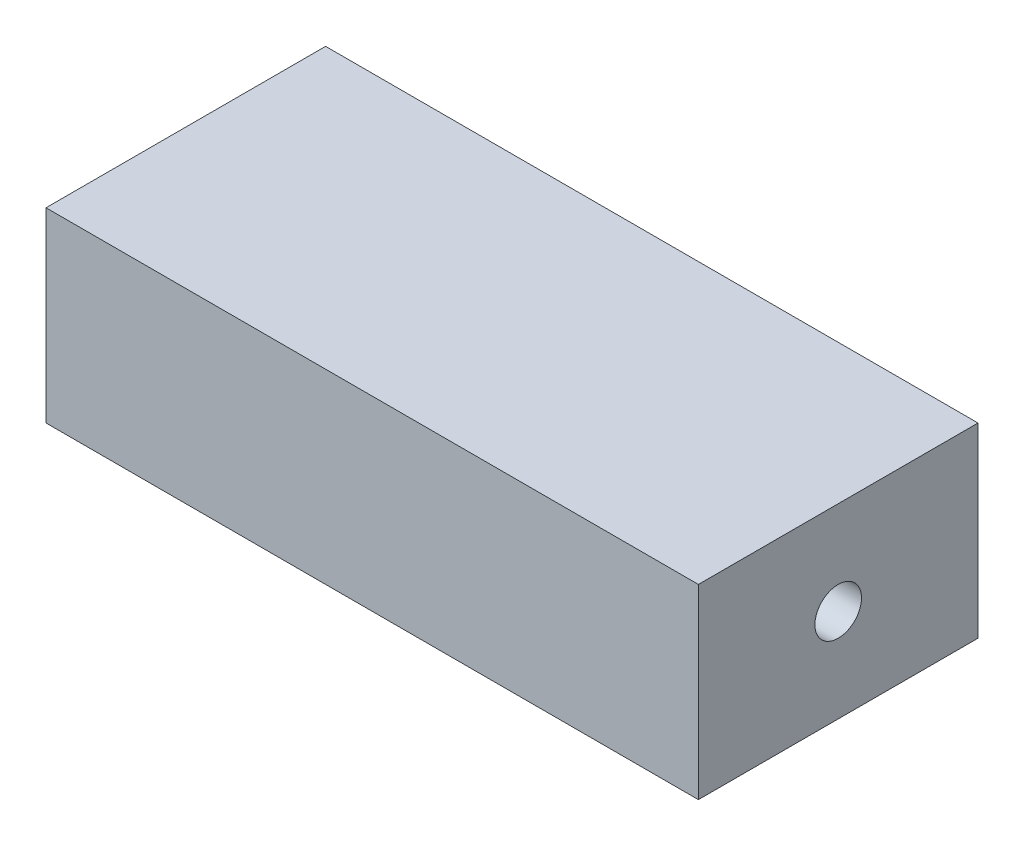
SolidWorks part; units mm, degrees
material "Balsa"
ref_plane "Front Plane" through (0, 0, 0) normal (0, 0, 1) x (1, 0, 0)
ref_plane "Top Plane" through (0, 0, 0) normal (0, 1, 0) x (1, 0, 0)
ref_plane "Right Plane" through (0, 0, 0) normal (1, 0, 0) x (0, 0, -1)
sketch "Sketch1" plane through (0, 0, 0) normal (0, 1, 0) x (1, 0, 0)
  line L1 (0, 0) -> (88.9, 0)
  line L2 (0, 0) -> (0, 38.1)
  line L3 (0, 38.1) -> (88.9, 38.1)
  line L4 (88.9, 0) -> (88.9, 38.1)
  dimension "D1" = 38.1
  dimension "D2" = 88.9
extrude "Boss-Extrude1" add sketch "Sketch1" along normal blind 25.4
sketch "Sketch2" plane through (88.9, 0, 0) normal (1, 0, 0) x (0, 0, -1)
  line L0 (0, 0) -> (38.1, 0) construction
  line L1 (38.1, 25.4) -> (38.1, 0) construction
  circle A0 centre (19.05, 12.7) radius 3.175
  dimension "D1" = 6.35
  dimension "D2" = 12.7
  dimension "D3" = 19.05
extrude "Cut-Extrude1" cut sketch "Sketch2" against normal through all
